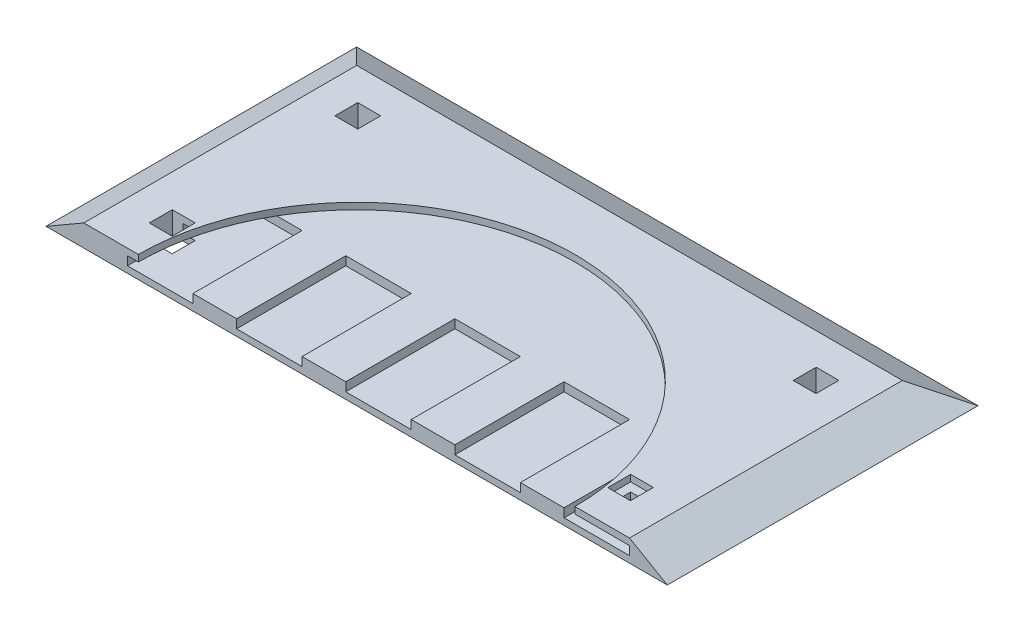
SolidWorks part; units mm, degrees
ref_plane "前视基准面" through (0, 0, 0) normal (0, 0, 1) x (1, 0, 0)
ref_plane "上视基准面" through (0, 0, 0) normal (0, 1, 0) x (1, 0, 0)
ref_plane "右视基准面" through (0, 0, 0) normal (1, 0, 0) x (0, 0, -1)
sketch "草图1" plane through (0, 0, 0) normal (0, 1, 0) x (1, 0, 0)
  line L0 (-125, 0) -> (125, 0)
  line L1 (-125, 125) -> (125, 125)
  line L2 (-125, 125) -> (-125, 0)
  line L4 (125, 125) -> (125, 0)
  line L5 (-125, 125) -> (125, -125) construction
  line L6 (-125, -125) -> (125, 125) construction
  point P0 (0, 0)
  dimension "D1" = 250
  dimension "D2" = 250
extrude "凸台-拉伸1" add sketch "草图1" along normal blind 10
sketch "草图2" plane through (0, 0, 0) normal (0, 0, 1) x (1, 0, 0)
  line L0 (-125, 7) -> (125, 7)
  line L1 (-75, 7) -> (-75, 3)
  line L2 (-125, 7) -> (-105, 7)
  line L3 (-125, 7) -> (-125, 3)
  line L4 (-125, 0) -> (125, 0)
  line L5 (125, 0) -> (125, 10)
  line L6 (125, 10) -> (-125, 10)
  line L7 (-125, 10) -> (-125, 0)
  line L8 (-125, 0) -> (125, 0)
  line L9 (125, 0) -> (125, 10)
  line L10 (125, 10) -> (-125, 10)
  line L11 (-125, 10) -> (-125, 0)
  line L12 (-125, 3) -> (-105, 3)
  line L13 (-105, 7) -> (-105, 3)
  line L14 (-105, 7) -> (-75, 7)
  line L15 (-105, 7) -> (-105, 3)
  line L16 (-105, 3) -> (-75, 3)
  line L17 (-75, 7) -> (-75, 3)
  line L18 (-75, 7) -> (-55, 7)
  line L19 (-55, 7) -> (-55, 3)
  line L20 (-75, 3) -> (-55, 3)
  line L21 (-55, 7) -> (-55, 3)
  line L22 (-55, 7) -> (-25, 7)
  line L23 (-25, 7) -> (-25, 3)
  line L24 (-55, 3) -> (-25, 3)
  line L25 (-25, 7) -> (-25, 3)
  line L26 (-25, 7) -> (-5, 7)
  line L27 (-5, 7) -> (-5, 3)
  line L28 (-25, 3) -> (-5, 3)
  line L29 (-5, 7) -> (-5, 3)
  line L30 (-5, 7) -> (25, 7)
  line L31 (25, 7) -> (25, 3)
  line L32 (-5, 3) -> (25, 3)
  line L33 (25, 7) -> (25, 3)
  line L34 (25, 7) -> (45, 7)
  line L35 (45, 7) -> (45, 3)
  line L36 (25, 3) -> (45, 3)
  line L37 (45, 7) -> (45, 3)
  line L38 (45, 7) -> (75, 7)
  line L39 (75, 7) -> (75, 3)
  line L40 (45, 3) -> (75, 3)
  line L41 (75, 7) -> (75, 3)
  line L42 (75, 7) -> (95, 7)
  line L43 (95, 7) -> (95, 3)
  line L44 (75, 3) -> (95, 3)
  line L45 (95, 7) -> (95, 3)
  line L46 (95, 7) -> (125, 7)
  line L47 (125, 7) -> (125, 3)
  line L48 (95, 3) -> (125, 3)
  dimension "D2" = 3
  dimension "D3" = 20
  dimension "D4" = 30
  dimension "D5" = 4
  dimension "D6" = 3
  dimension "D1" = 0
  dimension "D7" = 5
sketch "草图3" plane through (0, 10, 0) normal (0, 1, 0) x (1, 0, 0)
  line L0 (0, 125) -> (0, -49.5159)
  line L1 (-125, 125) -> (125, 125)
  line L2 (-125, 125) -> (-125, 0)
  line L3 (-125, 0) -> (125, 0)
  line L4 (125, 125) -> (125, 0)
  line L5 (-125, 125) -> (-105, 125)
  line L6 (-125, 125) -> (-125, 105)
  line L7 (-125, 105) -> (-105, 105)
  line L8 (-105, 125) -> (-105, 105)
  line L9 (-125, 0) -> (-105, 0)
  line L10 (-125, 0) -> (-125, 20)
  line L11 (-125, 20) -> (-105, 20)
  line L12 (-105, 0) -> (-105, 20)
  line L21 (-110, 110) -> (-100, 110)
  line L22 (-110, 110) -> (-110, 100)
  line L23 (-110, 100) -> (-100, 100)
  line L24 (-100, 110) -> (-100, 100)
  line L25 (-110, 110) -> (-100, 100) construction
  line L26 (-110, 100) -> (-100, 110) construction
  line L27 (-110, 25) -> (-100, 25)
  line L28 (-110, 25) -> (-110, 15)
  line L29 (-110, 15) -> (-100, 15)
  line L30 (-100, 25) -> (-100, 15)
  line L31 (-110, 25) -> (-100, 15) construction
  line L32 (-110, 15) -> (-100, 25) construction
  line L37 (112.5, 12.5) -> (97.5, 27.5) construction
  line L38 (112.5, 27.5) -> (97.5, 12.5) construction
  line L43 (115, 95) -> (95, 115) construction
  line L44 (115, 115) -> (95, 95) construction
  line L45 (-115, 115) -> (-95, 115)
  line L46 (-115, 115) -> (-115, 95)
  line L47 (-115, 95) -> (-95, 95)
  line L48 (-95, 115) -> (-95, 95)
  line L49 (-115, 115) -> (-95, 95) construction
  line L50 (-115, 95) -> (-95, 115) construction
  line L51 (-112.5, 27.5) -> (-97.5, 27.5)
  line L52 (-112.5, 27.5) -> (-112.5, 12.5)
  line L53 (-112.5, 12.5) -> (-97.5, 12.5)
  line L54 (-97.5, 27.5) -> (-97.5, 12.5)
  line L55 (-112.5, 27.5) -> (-97.5, 12.5) construction
  line L56 (-112.5, 12.5) -> (-97.5, 27.5) construction
  line L57 (110, 15) -> (100, 25) construction
  line L58 (110, 25) -> (100, 15) construction
  line L59 (110, 100) -> (100, 110) construction
  line L60 (110, 110) -> (100, 100) construction
  line L61 (97.5, 27.5) -> (97.5, 12.5)
  line L62 (112.5, 12.5) -> (97.5, 12.5)
  line L63 (112.5, 27.5) -> (112.5, 12.5)
  line L64 (112.5, 27.5) -> (97.5, 27.5)
  line L65 (95, 115) -> (95, 95)
  line L66 (115, 95) -> (95, 95)
  line L67 (115, 115) -> (115, 95)
  line L68 (115, 115) -> (95, 115)
  line L69 (100, 25) -> (100, 15)
  line L70 (110, 15) -> (100, 15)
  line L71 (110, 25) -> (110, 15)
  line L72 (110, 25) -> (100, 25)
  line L73 (100, 110) -> (100, 100)
  line L74 (110, 100) -> (100, 100)
  line L75 (110, 110) -> (110, 100)
  line L76 (110, 110) -> (100, 110)
  line L77 (105, 0) -> (105, 20)
  line L78 (125, 20) -> (105, 20)
  line L79 (125, 0) -> (125, 20)
  line L80 (125, 0) -> (105, 0)
  line L81 (105, 125) -> (105, 105)
  line L82 (125, 105) -> (105, 105)
  line L83 (125, 125) -> (125, 105)
  line L84 (125, 125) -> (105, 125)
  line L85 (125, 125) -> (125, 0)
  dimension "D1" = 20
  dimension "D2" = 20
  dimension "D3" = 20
  dimension "D4" = 20
  dimension "D9" = 10
  dimension "D10" = 10
  dimension "D11" = 10
  dimension "D12" = 10
  dimension "D17" = 20
  dimension "D18" = 20
  dimension "D19" = 15
  dimension "D20" = 15
sketch "草图4" plane through (0, 10, 0) normal (0, 1, 0) x (1, 0, 0)
  circle A0 centre (0, 0) radius 100
sketch "草图5" plane through (0, 10, 0) normal (0, 1, 0) x (1, 0, 0)
  line L1 (-110, 110) -> (-100, 110)
  line L2 (-110, 110) -> (-110, 100)
  line L3 (-110, 100) -> (-100, 100)
  line L4 (-100, 110) -> (-100, 100)
  line L5 (-110, 25) -> (-100, 25)
  line L6 (-110, 25) -> (-110, 15)
  line L7 (-110, 15) -> (-100, 15)
  line L8 (-100, 25) -> (-100, 15)
  line L9 (100, 110) -> (110, 110)
  line L10 (100, 110) -> (100, 100)
  line L11 (100, 100) -> (110, 100)
  line L12 (110, 110) -> (110, 100)
  line L13 (100, 25) -> (110, 25)
  line L14 (100, 25) -> (100, 15)
  line L15 (100, 15) -> (110, 15)
  line L16 (110, 25) -> (110, 15)
extrude "切除-拉伸1" cut sketch "草图5" against normal up to surface (10 mm away) up to face at (0, 0, -62.5)
sketch "草图6" plane through (0, 10, 0) normal (0, 1, 0) x (1, 0, 0)
  line L0 (-100, 0) -> (100, 0)
  arc A0 (100, 0) -> (-100, 0) centre (0, 0) ccw
extrude "切除-拉伸2" cut sketch "草图6" against normal blind 3
sketch "草图7" plane through (0, 0, 0) normal (0, 0, 1) x (1, 0, 0)
  line L1 (-105, 7) -> (-75, 7)
  line L2 (-105, 7) -> (-105, 3)
  line L3 (-105, 3) -> (-75, 3)
  line L4 (-75, 7) -> (-75, 3)
  line L5 (-55, 7) -> (-25, 7)
  line L6 (-55, 7) -> (-55, 3)
  line L7 (-55, 3) -> (-25, 3)
  line L8 (-25, 7) -> (-25, 3)
  line L9 (-5, 7) -> (25, 7)
  line L10 (-5, 7) -> (-5, 3)
  line L11 (-5, 3) -> (25, 3)
  line L12 (25, 7) -> (25, 3)
  line L13 (45, 7) -> (75, 7)
  line L14 (45, 7) -> (45, 3)
  line L15 (45, 3) -> (75, 3)
  line L16 (75, 7) -> (75, 3)
  line L17 (95, 7) -> (125, 7)
  line L18 (95, 7) -> (95, 3)
  line L19 (95, 3) -> (125, 3)
  line L20 (125, 7) -> (125, 3)
extrude "切除-拉伸3" cut sketch "草图7" against normal blind 50
sketch "草图8" plane through (-125, 0, 0) normal (-1, 0, 0) x (0, 0, 1)
  line L3 (-125, 10) -> (-125, 0)
  line L4 (-125, 0) -> (-142.3205, 0)
  line L5 (-142.3205, 0) -> (-125, 10)
  dimension "D1" = 30
extrude "凸台-拉伸3" add sketch "草图8" against normal up to surface (250 mm away) up to face at (125, 5, -43.75)
sketch "草图9" plane through (0, 0, 0) normal (0, 0, 1) x (1, 0, 0)
  line L0 (-125, 10) -> (-125, 0)
  line L1 (-125, 0) -> (-142.3205, 0)
  line L2 (-142.3205, 0) -> (-125, 10)
  line L3 (125, 10) -> (125, 0)
  line L4 (125, 0) -> (142.3205, 0)
  line L5 (142.3205, 0) -> (125, 10)
  dimension "D1" = 30
  dimension "D2" = 30
extrude "凸台-拉伸4" add sketch "草图9" against normal up to surface (142.3205 mm away)
sketch "草图10" plane through (0, 10, 0) normal (0, 1, 0) x (1, 0, 0)
  line L0 (-115, 95) -> (-95, 115) construction
  line L1 (-110, 100) -> (-99.5, 100)
  line L2 (-110, 100) -> (-110, 110.5)
  line L3 (-110, 110.5) -> (-99.5, 110.5)
  line L4 (-99.5, 100) -> (-99.5, 110.5)
  line L5 (-110, 110) -> (-100, 110) construction
  line L6 (-110, 100) -> (-99.5, 100)
  line L7 (-110, 100) -> (-110, 110.5)
  line L8 (-110, 110.5) -> (-99.5, 110.5)
  line L9 (-99.5, 100) -> (-99.5, 110.5)
  line L10 (-110.4987, 14.498) -> (-99.9987, 14.498)
  line L11 (-110.4987, 14.498) -> (-110.4987, 24.998)
  line L12 (-110.4987, 24.998) -> (-99.9987, 24.998)
  line L13 (-99.9987, 14.498) -> (-99.9987, 24.998)
  line L14 (-110.4987, 14.498) -> (-99.9987, 14.498)
  line L15 (-110.4987, 14.498) -> (-110.4987, 24.998)
  line L16 (-110.4987, 24.998) -> (-99.9987, 24.998)
  line L17 (-99.9987, 14.498) -> (-99.9987, 24.998)
  line L18 (99.4604, 99.5855) -> (109.9604, 99.5855)
  line L19 (99.4604, 99.5855) -> (99.4604, 110.0855)
  line L20 (99.4604, 110.0855) -> (109.9604, 110.0855)
  line L21 (109.9604, 99.5855) -> (109.9604, 110.0855)
  line L22 (99.6056, 14.4799) -> (110.1056, 14.4799)
  line L23 (99.6056, 14.4799) -> (99.6056, 24.9799)
  line L24 (99.6056, 24.9799) -> (110.1056, 24.9799)
  line L25 (110.1056, 14.4799) -> (110.1056, 24.9799)
  dimension "D1" = 0.5
sketch "草图11" plane through (0, 10, 0) normal (0, 1, 0) x (1, 0, 0)
  line L1 (-110, 110.5) -> (-99.5, 110.5)
  line L2 (-110, 110.5) -> (-110, 100)
  line L3 (-110, 100) -> (-99.5, 100)
  line L4 (-99.5, 110.5) -> (-99.5, 100)
  line L5 (-110, 15) -> (-99.5, 15)
  line L6 (-110, 15) -> (-110, 25.5209)
  line L7 (-110, 25.5209) -> (-99.5, 25.5209)
  line L8 (-99.5, 15) -> (-99.5, 25.5209)
  line L9 (100, 15) -> (110.4159, 15)
  line L10 (100, 15) -> (100, 25.5209)
  line L11 (100, 25.5209) -> (110.4159, 25.5209)
  line L12 (110.4159, 15) -> (110.4159, 25.5209)
  line L13 (100, 100) -> (110.4159, 100)
  line L14 (100, 100) -> (100, 110.5)
  line L15 (100, 110.5) -> (110.4159, 110.5)
  line L20 (110.4159, 100) -> (110.4159, 110.5)
extrude "切除-拉伸4" cut sketch "草图11" against normal through all
